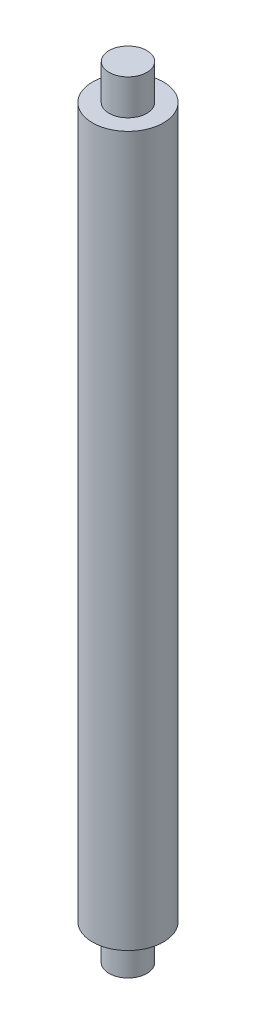
SolidWorks part; units mm, degrees
ref_plane "Front" through (0, 0, 0) normal (0, 0, 1) x (1, 0, 0)
ref_plane "Top" through (0, 0, 0) normal (0, 1, 0) x (1, 0, 0)
ref_plane "Right" through (0, 0, 0) normal (1, 0, 0) x (0, 0, -1)
sketch "Sketch1" plane through (0, 0, 0) normal (0, 1, 0) x (1, 0, 0)
  circle A0 centre (0, 0) radius 1.6
  dimension "D1" = 3.2
extrude "Boss-Extrude1" add sketch "Sketch1" along normal blind 3
sketch "Sketch2" plane through (0, 3, 0) normal (0, 1, 0) x (1, 0, 0)
  circle A0 centre (0, 0) radius 3
  dimension "D1" = 6
extrude "Boss-Extrude2" add sketch "Sketch2" along normal blind 60
sketch "Sketch3" plane through (0, 63, 0) normal (0, 1, 0) x (1, 0, 0)
  circle A0 centre (0, 0) radius 1.6
  dimension "D1" = 3.2
extrude "Boss-Extrude3" add sketch "Sketch3" along normal blind 3
